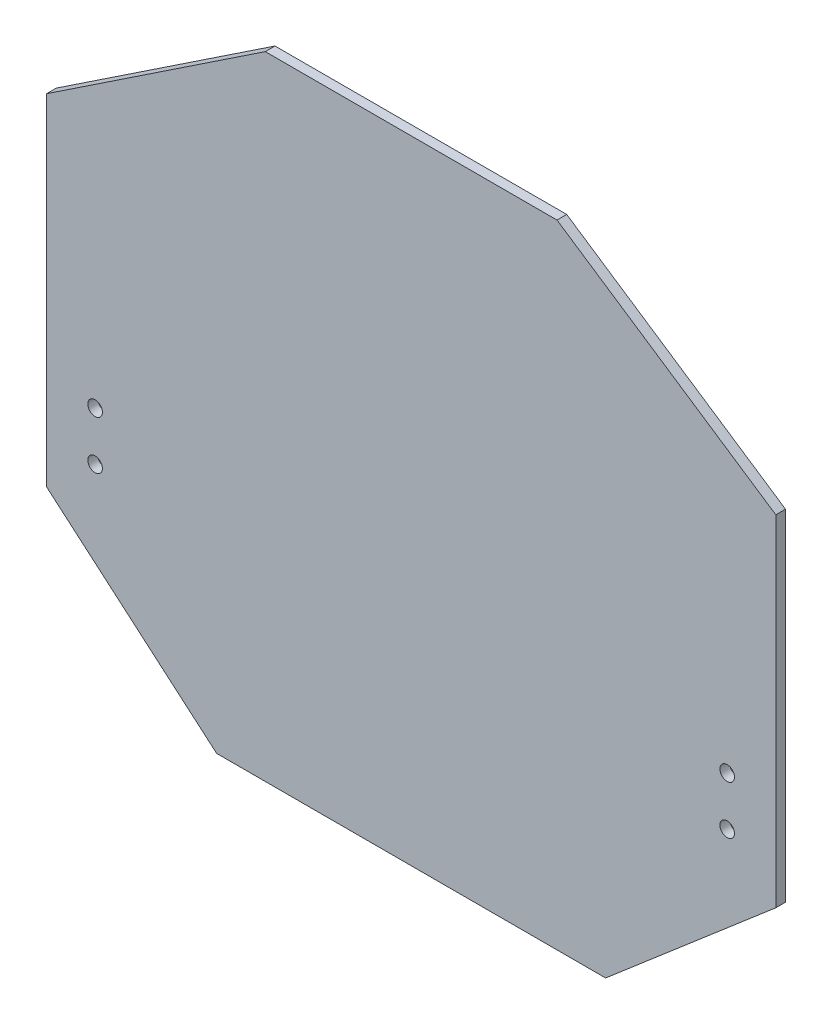
SolidWorks part; units mm, degrees
ref_plane "前视基准面" through (0, 0, 0) normal (0, 0, 1) x (1, 0, 0)
ref_plane "上视基准面" through (0, 0, 0) normal (0, 1, 0) x (1, 0, 0)
ref_plane "右视基准面" through (0, 0, 0) normal (1, 0, 0) x (0, 0, -1)
sketch "草图1" plane through (0, 0, 0) normal (0, 0, 1) x (1, 0, 0)
  line L0 (-75, 0) -> (-75, 70)
  line L1 (-75, 70) -> (-30, 100)
  line L2 (-30, 100) -> (30, 100)
  line L3 (0, 0) -> (0, 100) construction
  line L4 (-75, 0) -> (0, 0) construction
  line L5 (75, 0) -> (75, 70)
  line L6 (75, 70) -> (30, 100)
  line L7 (-75, 0) -> (-40, -30)
  line L8 (-40, -30) -> (40, -30)
  line L9 (75, 0) -> (40, -30)
  line L10 (-65, 0) -> (-65, 9) construction
  line L14 (-65, 9) -> (-65, 19) construction
  circle A0 centre (-65, 9) radius 1.5
  circle A1 centre (65, 9) radius 1.5
  circle A2 centre (-65, 19) radius 1.5
  circle A3 centre (65, 19) radius 1.5
  point P12 (0, -30)
  dimension "D1" = 3
  dimension "D2" = 130
  dimension "D3" = 100
  dimension "D4" = 70
  dimension "D5" = 30
  dimension "D6" = 80
  dimension "D7" = 60
  dimension "D8" = 9
  dimension "D9" = 10
  dimension "D11" = 10
  dimension "D10" = 2
extrude "凸台-拉伸1" add sketch "草图1" along normal blind 2
